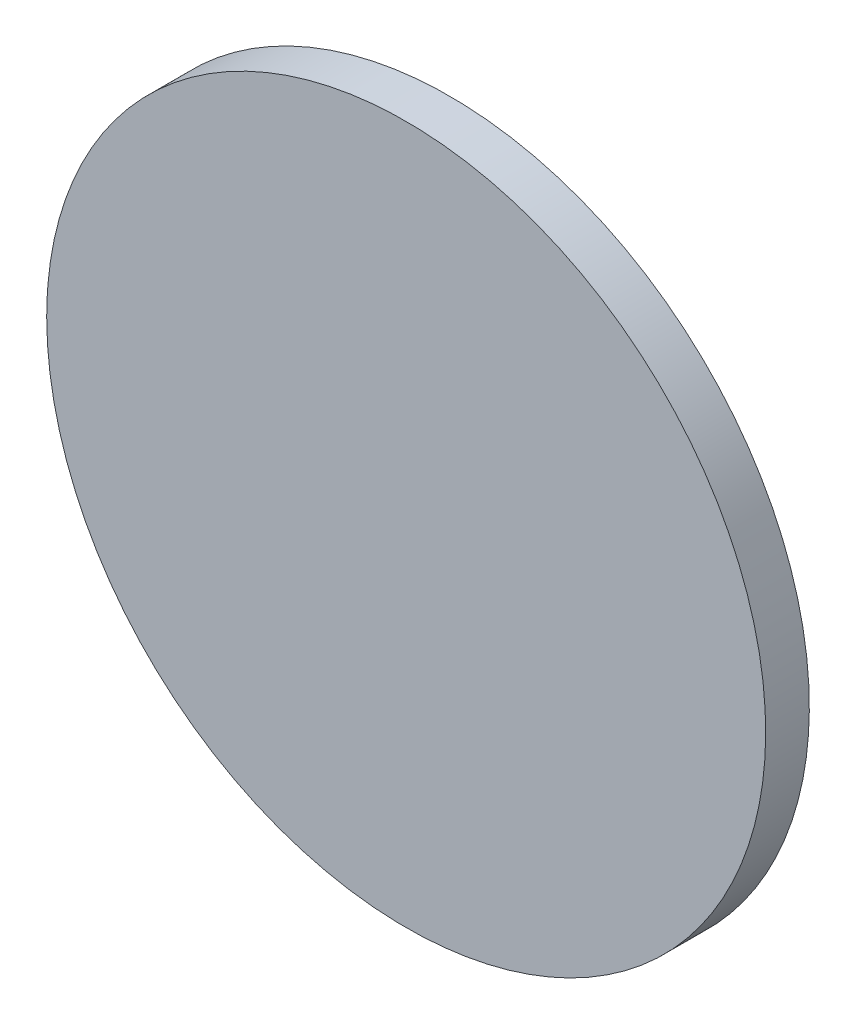
SolidWorks part; units mm, degrees
material "Acrylic (Medium-high impact)"
ref_plane "Front Plane" through (0, 0, 0) normal (0, 0, 1) x (1, 0, 0)
ref_plane "Top Plane" through (0, 0, 0) normal (0, 1, 0) x (1, 0, 0)
ref_plane "Right Plane" through (0, 0, 0) normal (1, 0, 0) x (0, 0, -1)
sketch "Sketch1" plane through (0, 0, 0) normal (0, 0, 1) x (1, 0, 0)
  point P0 (0, 0)
  ellipse B0 centre (0, 0) end of major axis (-26.1547, 0) minor radius 25.4
sketch_block_instance "Block1-1"
sketch_block "Block1"
sketch "Sketch2" plane through (0, 0, 0) normal (0, 0, 1) x (1, 0, 0)
  ellipse E0 centre (0, 0) end of major axis (-26.1547, 0) minor radius 25.4 construction
  ellipse E1 centre (0, 0) end of major axis (-26.1547, 0) minor radius 25.4
extrude "Boss-Extrude1" add sketch "Sketch2" along normal blind 3.175
